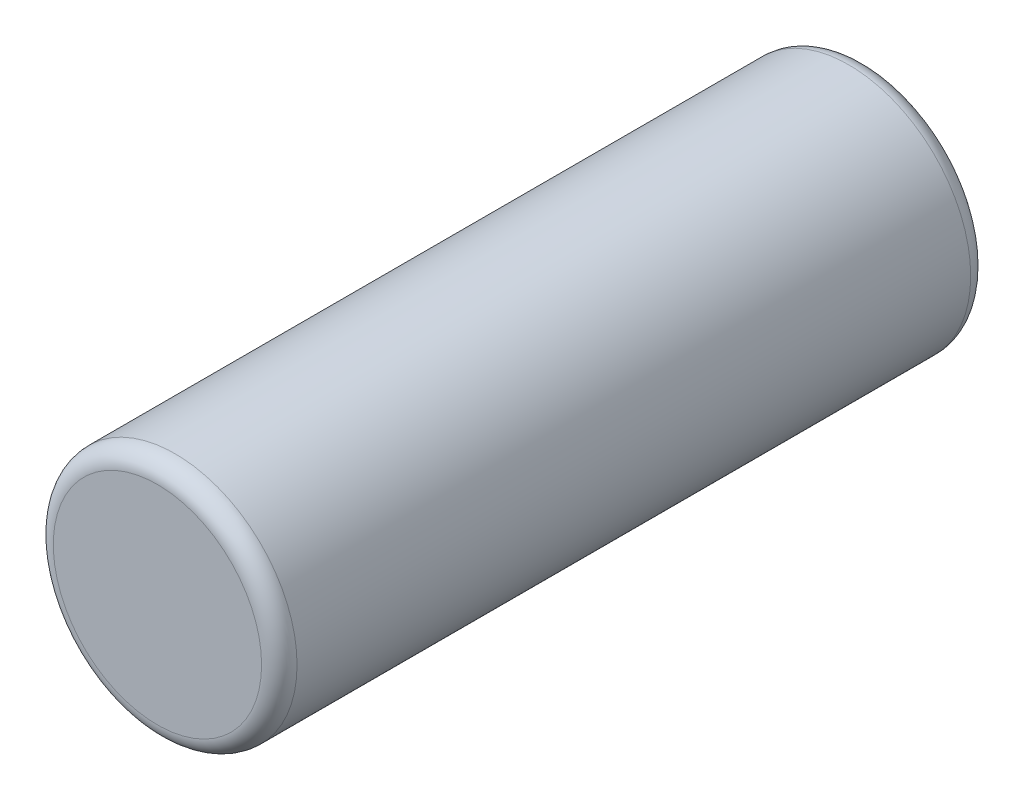
SolidWorks part; units mm, degrees
ref_plane "Front Plane" through (0, 0, 0) normal (0, 0, 1) x (1, 0, 0)
ref_plane "Top Plane" through (0, 0, 0) normal (0, 1, 0) x (1, 0, 0)
ref_plane "Right Plane" through (0, 0, 0) normal (1, 0, 0) x (0, 0, -1)
sketch "Sketch1" plane through (0, 0, 0) normal (0, 0, 1) x (1, 0, 0)
  circle A0 centre (0, 0) radius 1.375
  dimension "D1" = 2.75
extrude "Boss-Extrude1" add sketch "Sketch1" along normal blind 8
fillet "Fillet1" radius 0.2 2 edges at (1.375, 0, 8) (1.375, 0, 0)
